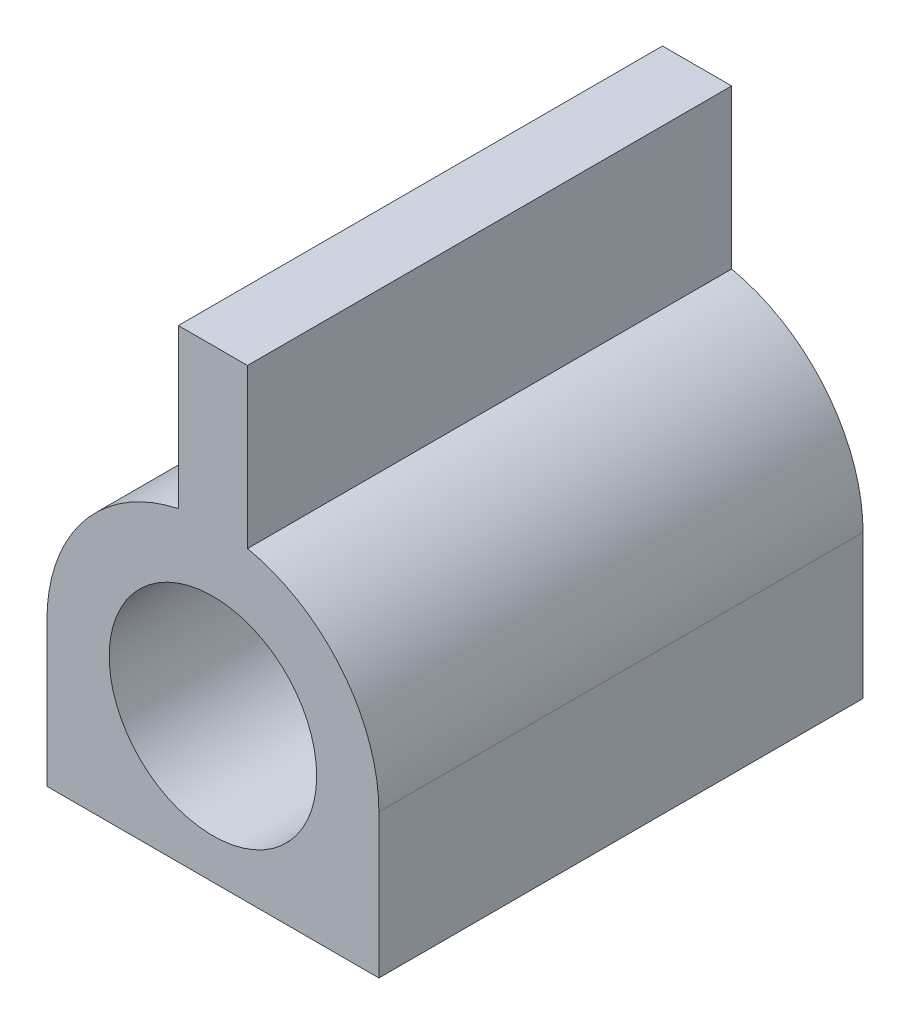
SolidWorks part; units mm, degrees
ref_plane "Front Plane" through (0, 0, 0) normal (0, 0, 1) x (1, 0, 0)
ref_plane "Top Plane" through (0, 0, 0) normal (0, 1, 0) x (1, 0, 0)
ref_plane "Right Plane" through (0, 0, 0) normal (1, 0, 0) x (0, 0, -1)
sketch "Sketch1" plane through (0, 0, 0) normal (0, 0, 1) x (1, 0, 0)
  line L0 (15.24, -13.208) -> (-15.24, -13.208)
  line L1 (-15.24, -13.208) -> (-15.24, 0)
  line L2 (15.24, 0) -> (15.24, -13.208)
  line L3 (-3.175, 14.9056) -> (-3.175, 29.464)
  line L4 (-3.175, 29.464) -> (3.175, 29.464)
  line L5 (3.175, 29.464) -> (3.175, 14.9056)
  line L6 (0, 29.464) -> (0, -13.208) construction
  arc A0 (-15.24, 0) -> (-3.175, 14.9056) centre (0, 0) cw
  circle A1 centre (0, 0) radius 9.525
  arc A2 (3.175, 14.9056) -> (15.24, 0) centre (0, 0) cw
  dimension "D1" = 19.05
  dimension "D2" = 30.48
  dimension "D3" = 42.672
  dimension "D4" = 13.208
  dimension "D5" = 6.35
extrude "Boss-Extrude1" add sketch "Sketch1" along normal mid plane 44.45
